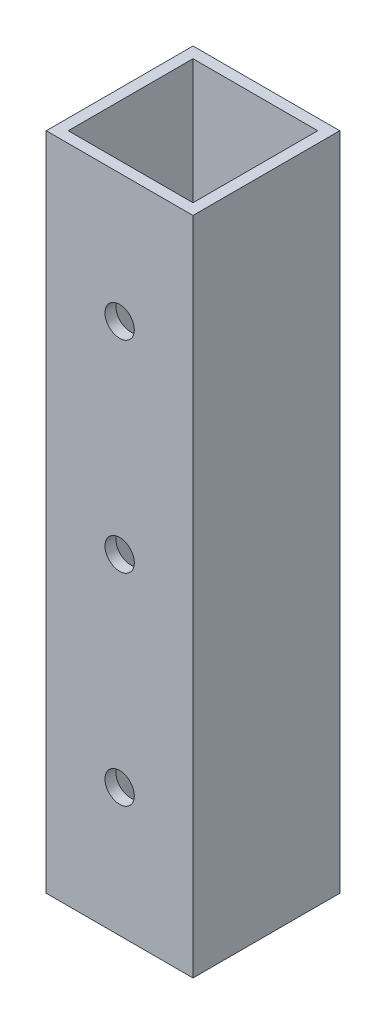
SolidWorks part; units mm, degrees
ref_plane "前视基准面" through (0, 0, 0) normal (0, 0, 1) x (1, 0, 0)
ref_plane "上视基准面" through (0, 0, 0) normal (0, 1, 0) x (1, 0, 0)
ref_plane "右视基准面" through (0, 0, 0) normal (1, 0, 0) x (0, 0, -1)
other "Configuration Table"
sketch "草图1" plane through (0, 0, 0) normal (0, 1, 0) x (1, 0, 0)
  line L1 (-8.5, 8.5) -> (8.5, 8.5)
  line L2 (-8.5, 8.5) -> (-8.5, -8.5)
  line L3 (-8.5, -8.5) -> (8.5, -8.5)
  line L4 (8.5, 8.5) -> (8.5, -8.5)
  line L5 (-8.5, 8.5) -> (8.5, -8.5) construction
  line L6 (-8.5, -8.5) -> (8.5, 8.5) construction
  line L7 (-10, 10) -> (10, 10)
  line L8 (-10, 10) -> (-10, -10)
  line L9 (-10, -10) -> (10, -10)
  line L10 (10, 10) -> (10, -10)
  line L11 (-10, 10) -> (10, -10) construction
  line L12 (-10, -10) -> (10, 10) construction
  point P0 (0, 0)
  point P5 (0, 0)
  dimension "D1" = 20
  dimension "D2" = 1.5
extrude "凸台-拉伸1" add sketch "草图1" along normal blind 90
sketch "草图2" plane through (0, 0, -10) normal (0, 0, -1) x (-1, 0, 0)
  line L0 (-10, 45) -> (0, 45) construction
  line L1 (-10, 90) -> (-10, 0) construction
  line L2 (0, 45) -> (0, 72.5) construction
  circle A0 centre (0, 72.5) radius 2
  circle A1 centre (0, 17.5) radius 2
  circle A2 centre (0, 45) radius 2
  dimension "D2" = 4
  dimension "D1" = 27.5
extrude "切除-拉伸1" cut sketch "草图2" against normal blind 100
